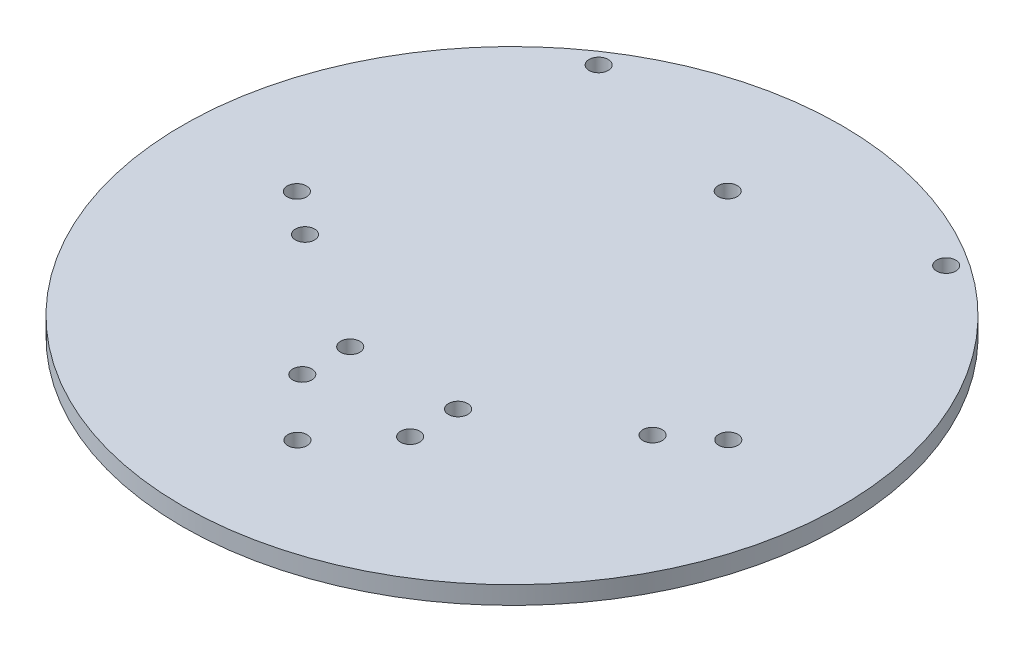
SolidWorks part; units mm, degrees
ref_plane "前视基准面" through (0, 0, 0) normal (0, 0, 1) x (1, 0, 0)
ref_plane "上视基准面" through (0, 0, 0) normal (0, 1, 0) x (1, 0, 0)
ref_plane "右视基准面" through (0, 0, 0) normal (1, 0, 0) x (0, 0, -1)
other "Configuration Table"
sketch "草图1" plane through (0, 0, 0) normal (0, 1, 0) x (1, 0, 0)
  line L0 (0, 0) -> (0, -9.7079)
  circle A0 centre (0, 0) radius 55
  circle A1 centre (35.9999, 0.0963) radius 1.6
  circle A2 centre (0.0962, -35.9022) radius 1.6
  circle A3 centre (-35.9024, 0.0014) radius 1.6
  circle A4 centre (0.0013, 36) radius 1.6
  circle A5 centre (-28.9987, 43.4573) radius 1.6
  circle A6 centre (29.0013, 43.4573) radius 1.6
  circle A7 centre (29, -5.5427) radius 1.6
  circle A8 centre (-29, -5.5427) radius 1.6
  circle A11 centre (-9, -26) radius 1.6
  circle A16 centre (-9, -18) radius 1.6
  circle A17 centre (9, -26) radius 1.6
  circle A18 centre (9, -18) radius 1.6
  point P14 (0.0488, 0.0489)
  dimension "D1" = 110
  dimension "D2" = 3.2
  dimension "D5" = 3.2
  dimension "D6" = 3.2
  dimension "D11" = 49
  dimension "D9" = 3.2
  dimension "D13" = 49
  dimension "D3" = 36
  dimension "D7" = 58
  dimension "D8" = 29
  dimension "D10" = 36
  dimension "D12" = 8
  dimension "D14" = 58
  dimension "D15" = 18
  dimension "D4" = 4
extrude "凸台-拉伸2" add sketch "草图1" along normal blind 3
